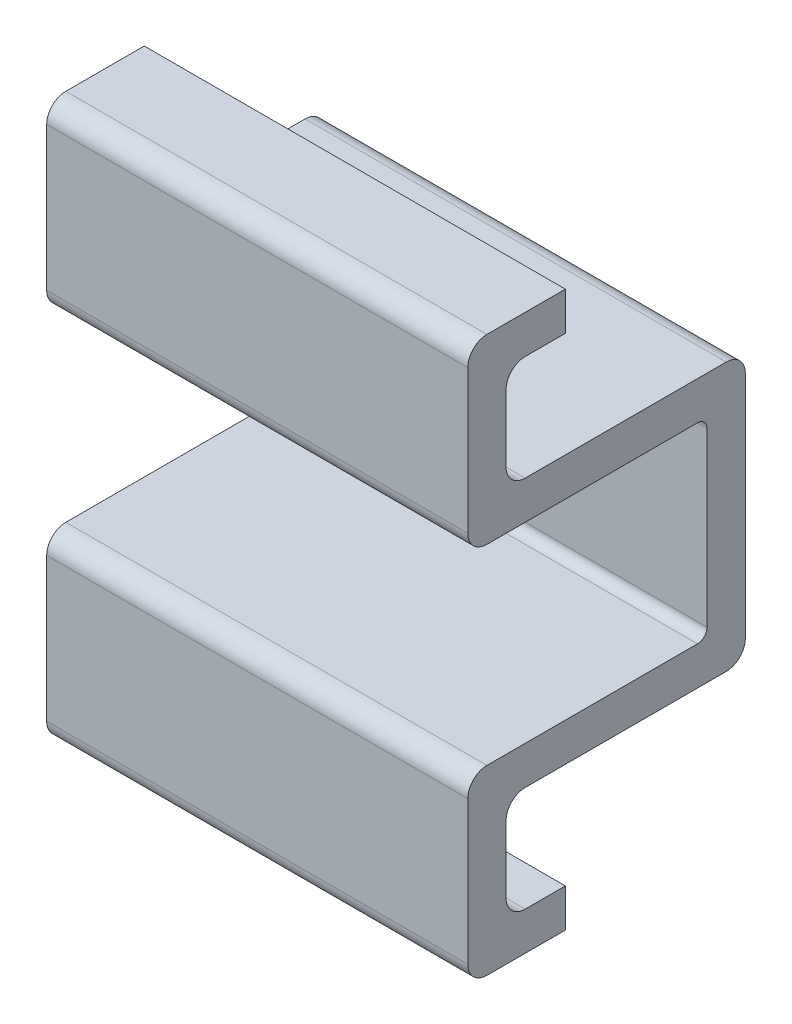
SolidWorks part; units mm, degrees
ref_plane "Front Plane" through (0, 0, 0) normal (0, 0, 1) x (1, 0, 0)
ref_plane "Top Plane" through (0, 0, 0) normal (0, 1, 0) x (1, 0, 0)
ref_plane "Right Plane" through (0, 0, 0) normal (1, 0, 0) x (0, 0, -1)
sketch "Sketch1" plane through (0, 0, 0) normal (0, 1, 0) x (1, 0, 0)
  line L0 (0, -63.3372) -> (0, 83.1005) construction
sketch "Sketch3" plane through (0, 0, 0) normal (1, 0, 0) x (0, 0, -1)
  line L0 (-5.7293, 5) -> (-5.7293, -5)
  line L1 (-63.3372, 0) -> (83.1005, 0) construction
  line L2 (-5.7293, -5) -> (-18.2293, -5)
  line L3 (-5.7293, 0) -> (-3.7293, 0)
  line L4 (-3.7293, 7) -> (-3.7293, -7)
  line L5 (-3.7293, -7) -> (-16.2293, -7)
  line L6 (-16.2293, -7) -> (-16.2293, -12.5)
  line L7 (-16.2293, -12.5) -> (-14.5224, -12.5)
  line L8 (-18.2293, -5) -> (-18.2293, -14.5)
  line L9 (-18.2293, -14.5) -> (-13.1317, -14.5)
  line L10 (-13.1317, -14.5) -> (-13.1317, -12.5)
  line L11 (-13.1317, -12.5) -> (-14.5224, -12.5)
  line L12 (-14.5224, 0) -> (7.8467, 0)
  line L13 (-13.1317, 14.5) -> (-13.1317, 12.5)
  line L14 (-18.2293, 14.5) -> (-13.1317, 14.5)
  line L15 (-18.2293, 5) -> (-18.2293, 14.5)
  line L16 (-5.7293, 5) -> (-18.2293, 5)
  line L17 (-3.7293, 7) -> (-16.2293, 7)
  line L18 (-16.2293, 7) -> (-16.2293, 12.5)
  line L19 (-16.2293, 12.5) -> (-14.5224, 12.5)
  line L20 (-13.1317, 12.5) -> (-14.5224, 12.5)
  dimension "D1" = 12.5
  dimension "D2" = 5
  dimension "D3" = 2
  dimension "D4" = 2
  dimension "D5" = 12.5
  dimension "D6" = 1.7068
  dimension "D7" = 5.5
  dimension "D8" = 9.5
extrude "Boss-Extrude1" add sketch "Sketch3" along normal blind 22 contours L10 L11 L7 L6 L5 L4 L3 L0 L2 L8 L9 | L20 L13 L14 L15 L16 L0 L3 L4 L17 L18 L19
fillet "Fillet1" radius 1 10 edges at (11, -7, 3.7293) (11, 7, 3.7293) (11, 14.5, 18.2293) (11, 5, 18.2293) (11, 12.5, 16.2293) (11, 7, 16.2293) (11, -7, 16.2293) (11, -12.5, 16.2293) (11, -14.5, 18.2293) (11, -5, 18.2293)
fillet "Fillet2" radius 0.5 2 edges at (11, 5, 5.7293) (11, -5, 5.7293)
